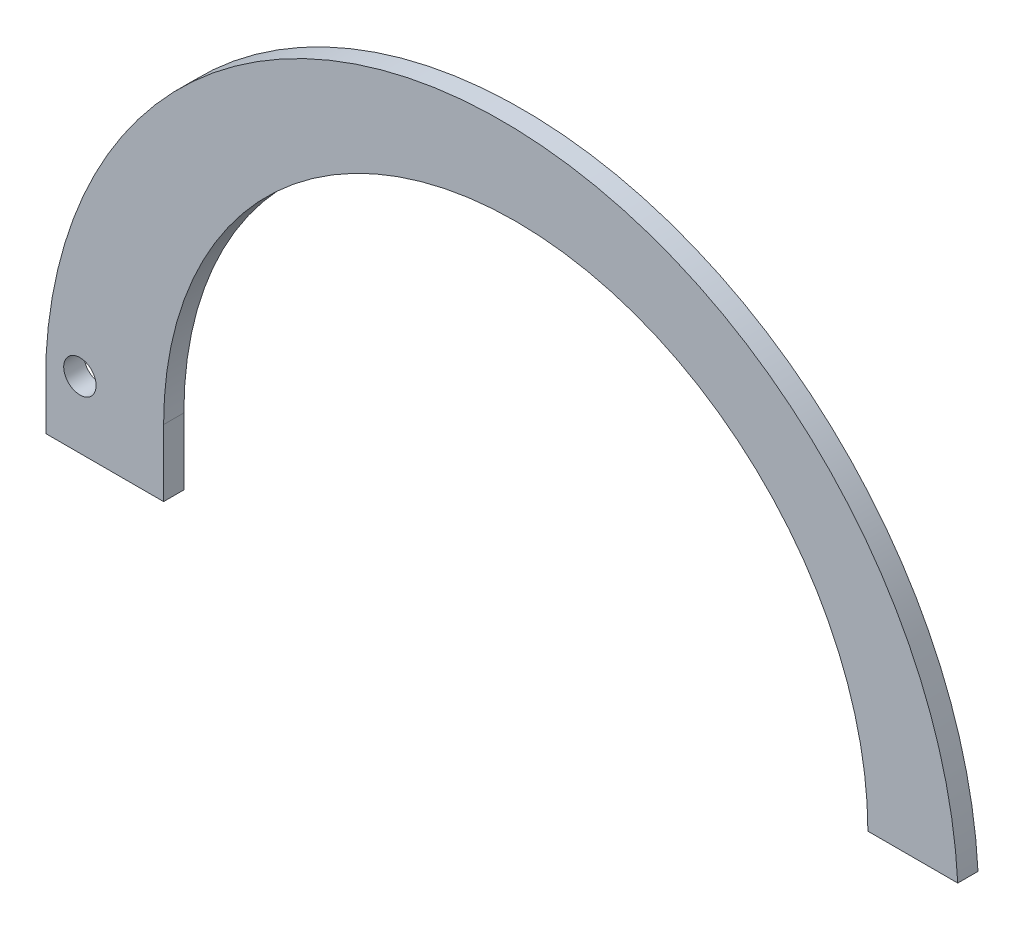
SolidWorks part; units mm, degrees
ref_plane "Front Plane" through (0, 0, 0) normal (0, 0, 1) x (1, 0, 0)
ref_plane "Top Plane" through (0, 0, 0) normal (0, 1, 0) x (1, 0, 0)
ref_plane "Right Plane" through (0, 0, 0) normal (1, 0, 0) x (0, 0, -1)
sketch "Sketch1" plane through (0, 0, 0) normal (0, 0, 1) x (1, 0, 0)
  line L0 (-8.3727, -16.4756) -> (20.6666, -16.4756)
  line L1 (20.6666, -16.4756) -> (20.6666, 0)
  line L2 (0, 0) -> (221.984, 0) construction
  line L3 (-8.3727, -16.4756) -> (-8.3727, 0)
  line L4 (194.5761, 0) -> (216.7634, 0)
  circle A0 centre (0, 0) radius 4
  arc A1 (20.6666, 0) -> (194.5761, 0) centre (107.6213, 0) cw
  arc A2 (-8.3727, 0) -> (216.7634, 0) centre (104.1954, -5.9883) cw
  dimension "D1" = 8
extrude "Boss-Extrude1" add sketch "Sketch1" along normal blind 5
